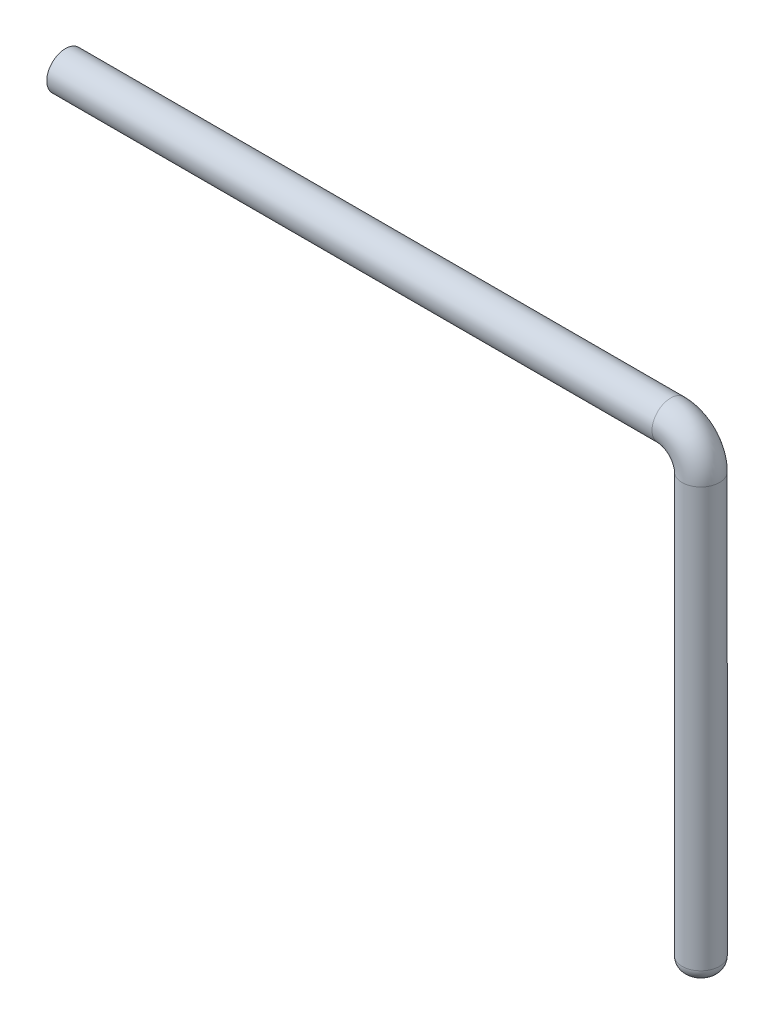
SolidWorks part; units mm, degrees
ref_plane "前视基准面" through (0, 0, 0) normal (0, 0, 1) x (1, 0, 0)
ref_plane "上视基准面" through (0, 0, 0) normal (0, 1, 0) x (1, 0, 0)
ref_plane "右视基准面" through (0, 0, 0) normal (1, 0, 0) x (0, 0, -1)
sketch "草图1" plane through (0, 0, 0) normal (0, 0, 1) x (1, 0, 0)
  line L0 (17.0785, 29.8628) -> (27.1185, 29.8628)
  line L2 (27.6185, 29.3628) -> (27.6185, 22.2128)
  arc A0 (27.1185, 29.8628) -> (27.6185, 29.3628) centre (27.1185, 29.3628) cw
  dimension "D1" = 0.5
sweep "扫描1" add path "草图1" circular profile diameter 0.62 parameters "D3"=0.62
fillet "圆角4" radius 0.2 1 edges at (27.6185, 22.2128, 0.31)
